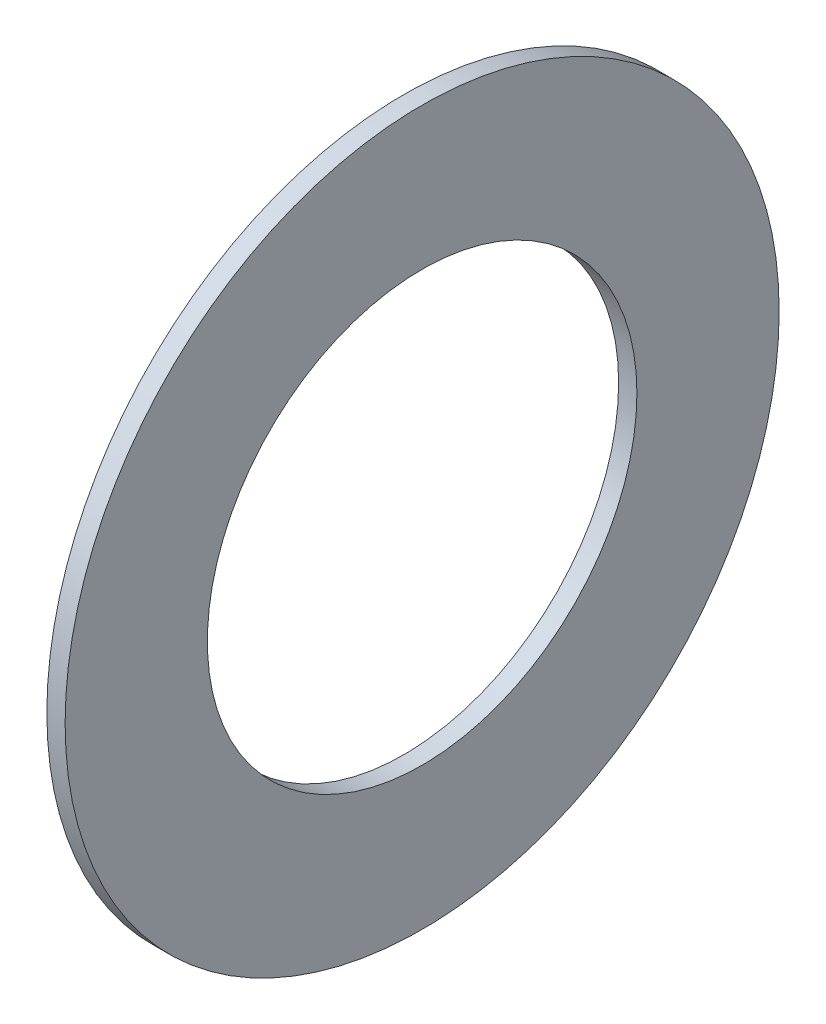
SolidWorks part; units mm, degrees
ref_plane "Front Plane" through (0, 0, 0) normal (0, 0, 1) x (1, 0, 0)
ref_plane "Top Plane" through (0, 0, 0) normal (0, 1, 0) x (1, 0, 0)
ref_plane "Right Plane" through (0, 0, 0) normal (1, 0, 0) x (0, 0, -1)
sketch "Sketch1" plane through (0, 0, 0) normal (1, 0, 0) x (0, 0, -1)
  circle A0 centre (0, 0) radius 15.875
  circle A1 centre (0, 0) radius 9.5504
  dimension "OD" = 31.75
  dimension "Shaft Dia" = 19.1008
extrude "Extrude1" add sketch "Sketch1" along normal blind 0.8128
